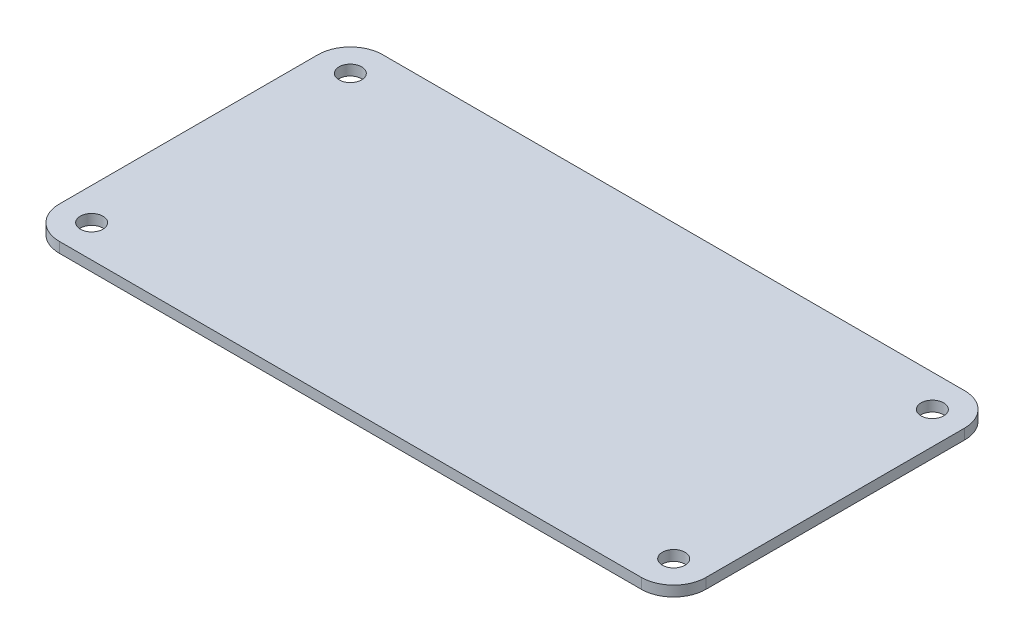
SolidWorks part; units mm, degrees
ref_plane "前视基准面" through (0, 0, 0) normal (0, 0, 1) x (1, 0, 0)
ref_plane "上视基准面" through (0, 0, 0) normal (0, 1, 0) x (1, 0, 0)
ref_plane "右视基准面" through (0, 0, 0) normal (1, 0, 0) x (0, 0, -1)
sketch "草图1" plane through (0, 0, 0) normal (0, 1, 0) x (1, 0, 0)
  line L1 (-50, 25) -> (50, 25)
  line L2 (-50, 25) -> (-50, -25)
  line L3 (-50, -25) -> (50, -25)
  line L4 (50, 25) -> (50, -25)
  line L5 (-50, 25) -> (50, -25) construction
  line L6 (-50, -25) -> (50, 25) construction
  circle A0 centre (-45, 20) radius 1.75
  circle A1 centre (45, 20) radius 1.75
  circle A2 centre (45, -20) radius 1.75
  circle A3 centre (-45, -20) radius 1.75
  point P0 (0, 0)
  dimension "D3" = 5
  dimension "D5" = 3.5
  dimension "D1" = 50
  dimension "D2" = 100
  dimension "D4" = 5
  dimension "D6" = 2
  dimension "D7" = 2
extrude "凸台-拉伸1" add sketch "草图1" along normal blind 1.6
fillet "圆角1" radius 5 4 edges at (-50, 0.8, 25) (50, 0.8, 25) (50, 0.8, -25) (-50, 0.8, -25)
